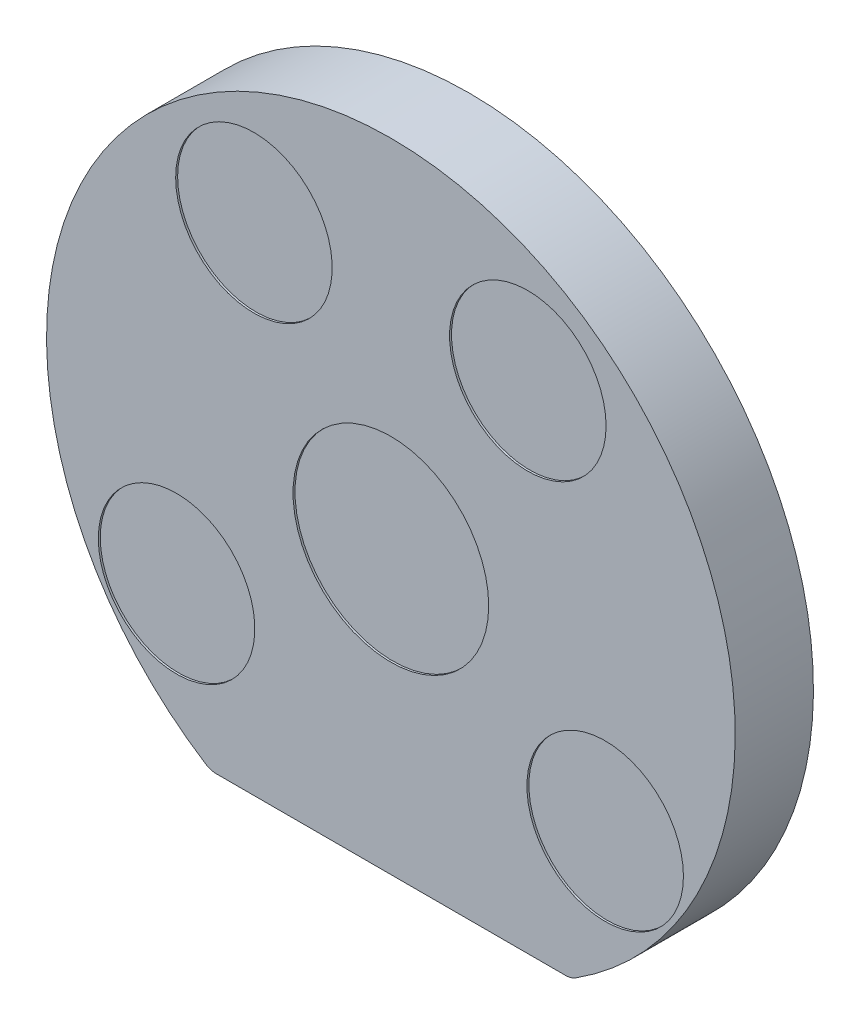
SolidWorks part; units mm, degrees
material "ABS"
ref_plane "Front Plane" through (0, 0, 0) normal (0, 0, 1) x (1, 0, 0)
ref_plane "Top Plane" through (0, 0, 0) normal (0, 1, 0) x (1, 0, 0)
ref_plane "Right Plane" through (0, 0, 0) normal (1, 0, 0) x (0, 0, -1)
sketch "ReferenceSketch" plane through (0, 0, 0) normal (0, 0, -1) x (1, 0, 0)
  line L0 (0, 97.4246) -> (0, -108.8317) construction
  line L1 (-109.4364, 0) -> (110.4876, 0) construction
  line L2 (0, 0) -> (76.2102, 44) construction
  line L3 (0, 0) -> (62.2254, -62.2254) construction
  line L4 (0, 0) -> (-76.2102, 44) construction
  line L5 (0, 0) -> (-62.2254, -62.2254) construction
  circle A0 centre (0, 0) radius 88 construction
  dimension "D1" = 176
  dimension "D2" = 60
  dimension "D3" = 60
  dimension "D4" = 45
  dimension "D5" = 45
sketch "Sketch2" plane through (0, 0, 0) normal (0, 0, 1) x (1, 0, 0)
  line L0 (-46.0326, -75) -> (46.0326, -75)
  circle A0 centre (0, 0) radius 88
  dimension "D1" = 176
  dimension "D2" = 75
extrude "Boss-Extrude1" add sketch "Sketch2" against normal blind 20 contours L0 A0
sketch "Sketch3" plane through (0, 0, -20) normal (0, 0, -1) x (-1, 0, 0)
  line L2 (-43.1161, -65) -> (43.1161, -65)
  line L3 (-43.1161, -65) -> (43.1161, -65)
  arc A2 (43.1161, -65) -> (-43.1161, -65) centre (0, 0) ccw
  arc A3 (43.1161, -65) -> (-43.1161, -65) centre (0, 0) ccw
  dimension "D1" = 10
extrude "Cut-Extrude1" cut sketch "Sketch3" against normal blind 17
sketch "Sketch4" plane through (0, 0, 0) normal (0, 0, 1) x (1, 0, 0)
  line L0 (0, 92.0809) -> (0, -87.3463) construction
  line L1 (-46.0326, -75) -> (46.0326, -75) construction
  circle A0 centre (0, -3) radius 25
  circle A1 centre (-54.77, -38) radius 20
  circle A2 centre (35, 51.77) radius 20
  circle A3 centre (54.77, -38) radius 20
  circle A4 centre (-35, 51.77) radius 20
  point P13 (0, 0)
  point P14 (0, 0)
  point P15 (0, 0)
  point P16 (0, -8.1304)
  dimension "D1" = 50
  dimension "D2" = 40
  dimension "D3" = 54.77
  dimension "D4" = 35
  dimension "D5" = 35
  dimension "D6" = 54.77
  dimension "D7" = 72
extrude "Cut-Extrude2" cut sketch "Sketch4" against normal blind 0.5
fillet "Fillet1" radius 10 2 edges at (43.1161, -65, -11.5) (-43.1161, -65, -11.5)
fillet "Fillet2" radius 5 2 edges at (-46.0326, -75, -10) (46.0326, -75, -10)
